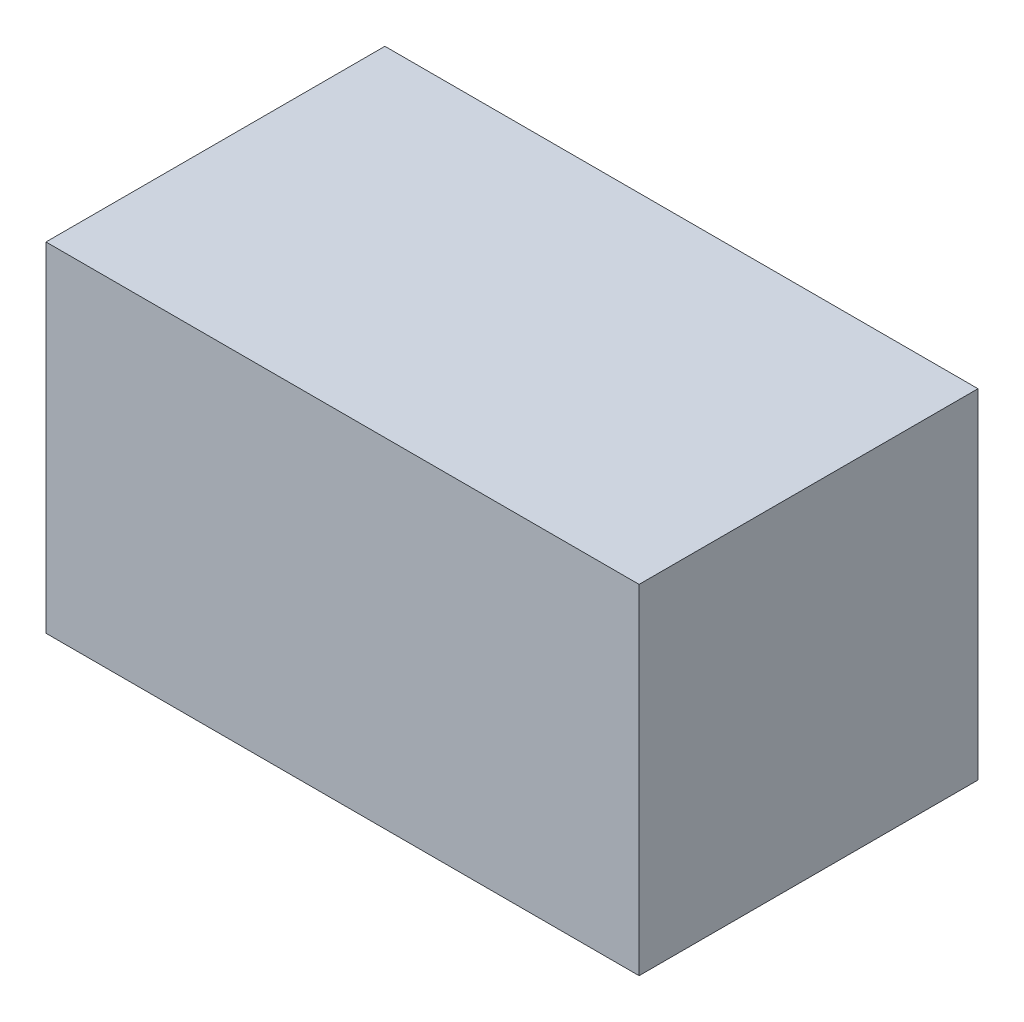
SolidWorks part; units mm, degrees
ref_plane "Front Plane" through (0, 0, 0) normal (0, 0, 1) x (1, 0, 0)
ref_plane "Top Plane" through (0, 0, 0) normal (0, 1, 0) x (1, 0, 0)
ref_plane "Right Plane" through (0, 0, 0) normal (1, 0, 0) x (0, 0, -1)
sketch "Sketch1" plane through (0, 0, 0) normal (0, 1, 0) x (1, 0, 0)
  line L1 (-44.45, -25.4) -> (44.45, -25.4)
  line L2 (-44.45, -25.4) -> (-44.45, 25.4)
  line L3 (-44.45, 25.4) -> (44.45, 25.4)
  line L4 (44.45, -25.4) -> (44.45, 25.4)
  line L5 (-44.45, -25.4) -> (44.45, 25.4) construction
  line L6 (-44.45, 25.4) -> (44.45, -25.4) construction
  point P0 (0, 0)
  dimension "D1" = 88.9
  dimension "D2" = 50.8
extrude "Boss-Extrude2" add sketch "Sketch1" along normal blind 50.8
